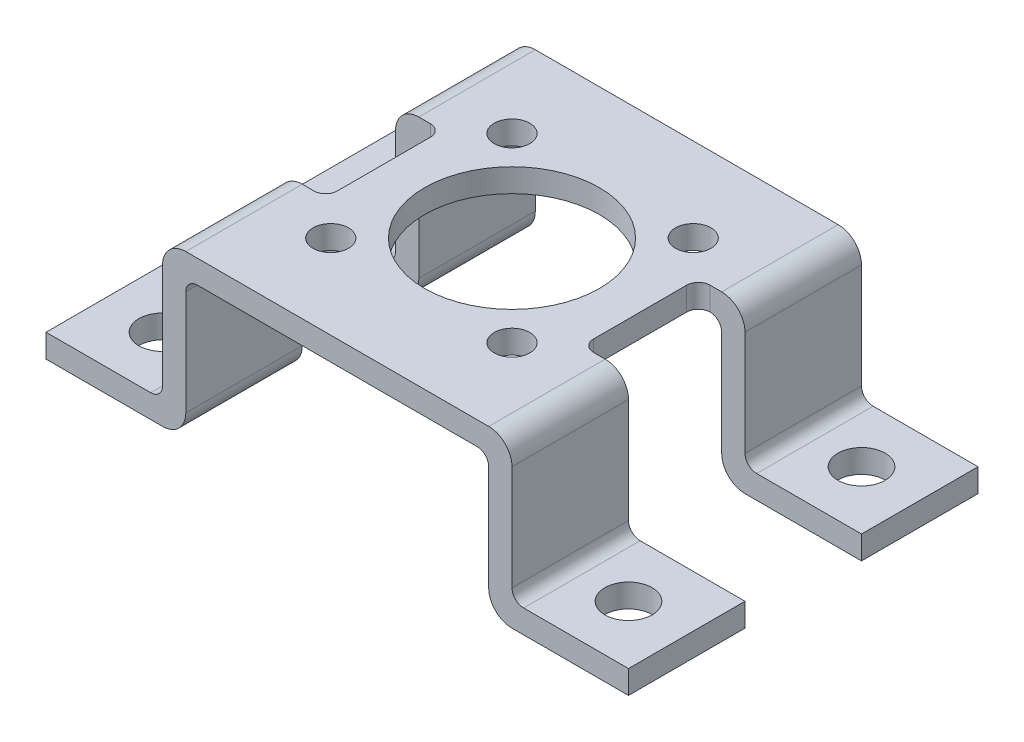
SolidWorks part; units mm, degrees
material "AISI 304"
ref_plane "Front Plane" through (0, 0, 0) normal (0, 0, 1) x (1, 0, 0)
ref_plane "Top Plane" through (0, 0, 0) normal (0, 1, 0) x (1, 0, 0)
ref_plane "Right Plane" through (0, 0, 0) normal (1, 0, 0) x (0, 0, -1)
sketch "Sketch1" plane through (0, 0, 0) normal (0, 1, 0) x (1, 0, 0)
  line L1 (-15, 15) -> (15, 15)
  line L2 (-15, 15) -> (-15, -15)
  line L3 (-15, -15) -> (15, -15)
  line L4 (15, 15) -> (15, -15)
  line L5 (-15, 15) -> (15, -15) construction
  line L6 (-15, -15) -> (15, 15) construction
  circle A0 centre (0, 0) radius 7.5
  circle A1 centre (0, 0) radius 11 construction
  circle A2 centre (-7.7782, 7.7782) radius 1.525
  circle A3 centre (7.7782, 7.7782) radius 1.525
  circle A4 centre (-7.7782, -7.7782) radius 1.525
  circle A5 centre (7.7782, -7.7782) radius 1.525
  point P0 (0, 0)
  point P13 (7.7782, 7.7782)
  point P16 (-7.7782, -7.7782)
  point P19 (7.7782, -7.7782)
  dimension "D3" = 15
  dimension "D4" = 22
  dimension "D5" = 3.05
  dimension "D6" = 3.05
  dimension "D7" = 3.05
  dimension "D8" = 3.05
  dimension "D1" = 30
  dimension "D2" = 30
extrude "Boss-Extrude1" add sketch "Sketch1" along normal blind 2
sketch "Sketch3" plane through (0, 0, 0) normal (0, -1, 0) x (1, 0, 0)
  line L0 (0, 16.1048) -> (0, -17.0212) construction
  line L1 (-20.4578, 0) -> (18.7867, 0) construction
  line L2 (-15, 15) -> (-13, 15)
  line L3 (-15, 15) -> (15, 15) construction
  line L4 (-13, 15) -> (-13, 5)
  line L5 (-13, 5) -> (-15, 5)
  line L6 (-15, -15) -> (-15, 15) construction
  line L7 (-15, 5) -> (-15, 15)
  line L8 (13, 5) -> (15, 5)
  line L9 (13, 15) -> (13, 5)
  line L10 (15, 15) -> (13, 15)
  line L11 (15, 5) -> (15, 15)
  line L12 (13, -15) -> (13, -5)
  line L13 (15, -15) -> (13, -15)
  line L14 (15, -5) -> (15, -15)
  line L15 (13, -5) -> (15, -5)
  line L16 (-13, -5) -> (-15, -5)
  line L17 (-13, -15) -> (-13, -5)
  line L18 (-15, -15) -> (-13, -15)
  line L19 (-15, -5) -> (-15, -15)
  dimension "D1" = 2
  dimension "D2" = 10
extrude "Boss-Extrude2" add sketch "Sketch3" along normal blind 10
sketch "Sketch4" plane through (0, -10, 0) normal (0, -1, 0) x (1, 0, 0)
  line L0 (0, 15.7005) -> (0, -16.4552) construction
  line L1 (-18.0589, 0) -> (17.9781, 0) construction
  line L2 (-13, 15) -> (-25, 15)
  line L3 (-25, 15) -> (-25, 5)
  line L4 (-25, 5) -> (-13, 5)
  line L5 (-13, 5) -> (-13, 15)
  line L6 (25, 5) -> (13, 5)
  line L7 (25, 15) -> (25, 5)
  line L8 (13, 15) -> (25, 15)
  line L9 (13, 5) -> (13, 15)
  line L10 (25, -15) -> (25, -5)
  line L11 (13, -15) -> (25, -15)
  line L12 (13, -5) -> (13, -15)
  line L13 (25, -5) -> (13, -5)
  line L14 (-25, -5) -> (-13, -5)
  line L15 (-25, -15) -> (-25, -5)
  line L16 (-13, -15) -> (-25, -15)
  line L17 (-13, -5) -> (-13, -15)
  line L18 (-15, 5) -> (-25, 15) construction
  line L19 (-25, 5) -> (-15, 15) construction
  circle A0 centre (-20, 10) radius 2.025
  circle A1 centre (20, 10) radius 2.025
  circle A2 centre (20, -10) radius 2.025
  circle A3 centre (-20, -10) radius 2.025
  dimension "D2" = 4.05
  dimension "D1" = 12
extrude "Boss-Extrude3" add sketch "Sketch4" along normal blind 2
sketch "Sketch5" plane through (0, 0, 0) normal (0, -1, 0) x (1, 0, 0)
  line L4 (0, 17.8946) -> (0, -17.2697) construction
  line L9 (-15, 5) -> (-11, 5)
  line L10 (-11, 5) -> (-11, -5)
  line L11 (-11, -5) -> (-15, -5)
  line L12 (-15, -5) -> (-15, 5)
  line L13 (11, -5) -> (15, -5)
  line L14 (11, 5) -> (11, -5)
  line L15 (15, 5) -> (11, 5)
  line L16 (15, -5) -> (15, 5)
  dimension "D1" = 4
extrude "Cut-Extrude1" cut sketch "Sketch5" against normal through all
fillet "Fillet1" radius 2 7 edges at (13, -12, 10) (13, -12, -10) (-13, -12, 10) (-13, -12, -10) (15, 2, 10) (-15, 2, 10) (-15, 2, -10)
fillet "Fillet2" radius 1 8 edges at (-13, 0, 10) (-15, -10, 10) (13, 0, 10) (15, -10, 10) (13, 0, -10) (15, -10, -10) (-13, 0, -10) (-15, -10, -10)
fillet "Fillet3" radius 1 4 edges at (-11, 1, -5) (11, 1, -5) (11, 1, 5) (-11, 1, 5)
